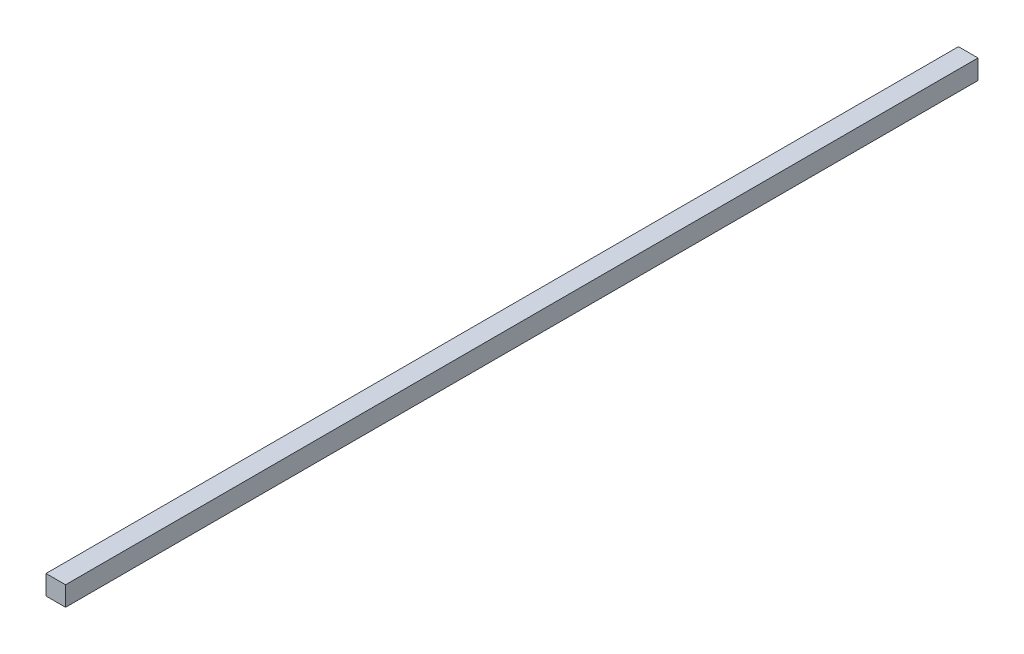
SolidWorks part; units mm, degrees
ref_plane "前视基准面" through (0, 0, 0) normal (0, 0, 1) x (1, 0, 0)
ref_plane "上视基准面" through (0, 0, 0) normal (0, 1, 0) x (1, 0, 0)
ref_plane "右视基准面" through (0, 0, 0) normal (1, 0, 0) x (0, 0, -1)
sketch "草图1" plane through (0, 0, 0) normal (0, 0, 1) x (1, 0, 0)
  line L1 (-15, 15) -> (15, 15)
  line L2 (-15, 15) -> (-15, -15)
  line L3 (-15, -15) -> (15, -15)
  line L4 (15, 15) -> (15, -15)
  line L5 (-15, 15) -> (15, -15) construction
  line L6 (-15, -15) -> (15, 15) construction
  point P0 (0, 0)
  dimension "D1" = 30
  dimension "D2" = 30
extrude "凸台-拉伸1" add sketch "草图1" along normal blind 1400
